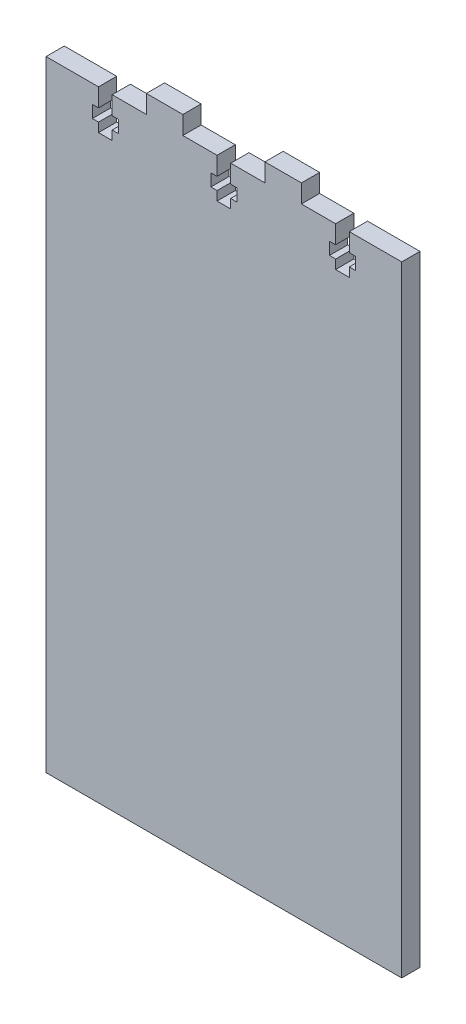
SolidWorks part; units mm, degrees
ref_plane "前视基准面" through (0, 0, 0) normal (0, 0, 1) x (1, 0, 0)
ref_plane "上视基准面" through (0, 0, 0) normal (0, 1, 0) x (1, 0, 0)
ref_plane "右视基准面" through (0, 0, 0) normal (1, 0, 0) x (0, 0, -1)
sketch "草图1" plane through (0, 0, 0) normal (0, 0, 1) x (1, 0, 0)
  line L0 (0, 20) -> (39, 20) construction
  line L2 (-39, 90) -> (-39, -46)
  line L3 (-39, -46) -> (39, -46)
  line L4 (39, 90) -> (39, -46)
  line L5 (0, 20) -> (-39, 20) construction
  line L6 (39, 90) -> (27.5, 90)
  line L7 (-27.5, 90) -> (-39, 90)
  line L59 (-39, 22) -> (-46.9885, 22) construction
  line L60 (-13, 94) -> (-13, 82.6313) construction
  line L61 (-26, 90) -> (-27.5, 90) construction
  line L62 (-26, 90) -> (-26, 81.3) construction
  line L63 (26, 90) -> (26, 81.3) construction
  line L64 (26, 90) -> (27.5, 90) construction
  line L65 (13, 94) -> (13, 82.6313) construction
  line L66 (0, 90) -> (-1.5, 90) construction
  line L67 (0, 90) -> (0, 81.3) construction
  line L68 (-9, 90) -> (-1.5, 90)
  line L69 (-9, 90) -> (-9, 94)
  line L70 (-9, 94) -> (-17, 94)
  line L71 (-17, 94) -> (-17, 90)
  line L72 (-24.5, 83.3) -> (-24.5, 81.3)
  line L73 (-23.15, 83.3) -> (-24.5, 83.3)
  line L74 (-24.5, 86) -> (-23.15, 86)
  line L75 (-23.15, 86) -> (-23.15, 83.3)
  line L76 (-24.5, 90) -> (-24.5, 86)
  line L77 (-27.5, 81.3) -> (-24.5, 81.3)
  line L78 (-27.5, 83.3) -> (-27.5, 81.3)
  line L79 (-28.85, 83.3) -> (-27.5, 83.3)
  line L80 (-28.85, 86) -> (-28.85, 83.3)
  line L81 (-27.5, 86) -> (-28.85, 86)
  line L82 (-27.5, 90) -> (-27.5, 86)
  line L83 (-17, 90) -> (-24.5, 90)
  line L84 (17, 90) -> (24.5, 90)
  line L85 (1.5, 90) -> (9, 90)
  line L86 (27.5, 90) -> (27.5, 86)
  line L87 (27.5, 86) -> (28.85, 86)
  line L88 (28.85, 86) -> (28.85, 83.3)
  line L89 (28.85, 83.3) -> (27.5, 83.3)
  line L90 (27.5, 83.3) -> (27.5, 81.3)
  line L91 (27.5, 81.3) -> (24.5, 81.3)
  line L92 (24.5, 90) -> (24.5, 86)
  line L93 (23.15, 86) -> (23.15, 83.3)
  line L94 (24.5, 86) -> (23.15, 86)
  line L95 (23.15, 83.3) -> (24.5, 83.3)
  line L96 (24.5, 83.3) -> (24.5, 81.3)
  line L97 (17, 94) -> (17, 90)
  line L98 (9, 94) -> (17, 94)
  line L99 (9, 90) -> (9, 94)
  line L100 (1.5, 83.3) -> (1.5, 81.3)
  line L101 (2.85, 83.3) -> (1.5, 83.3)
  line L102 (1.5, 86) -> (2.85, 86)
  line L103 (2.85, 86) -> (2.85, 83.3)
  line L104 (1.5, 90) -> (1.5, 86)
  line L105 (-1.5, 81.3) -> (1.5, 81.3)
  line L106 (-1.5, 83.3) -> (-1.5, 81.3)
  line L107 (-2.85, 83.3) -> (-1.5, 83.3)
  line L108 (-2.85, 86) -> (-2.85, 83.3)
  line L109 (-1.5, 86) -> (-2.85, 86)
  line L110 (-1.5, 90) -> (-1.5, 86)
  line L112 (-24.5, 90) -> (-17, 90)
  line L113 (-1.5, 90) -> (-9, 90)
  line L114 (1.5, 90) -> (9, 90)
  line L115 (17, 90) -> (24.5, 90)
  dimension "D6" = 39
extrude "凸台-拉伸1" add sketch "草图1" along normal blind 4
